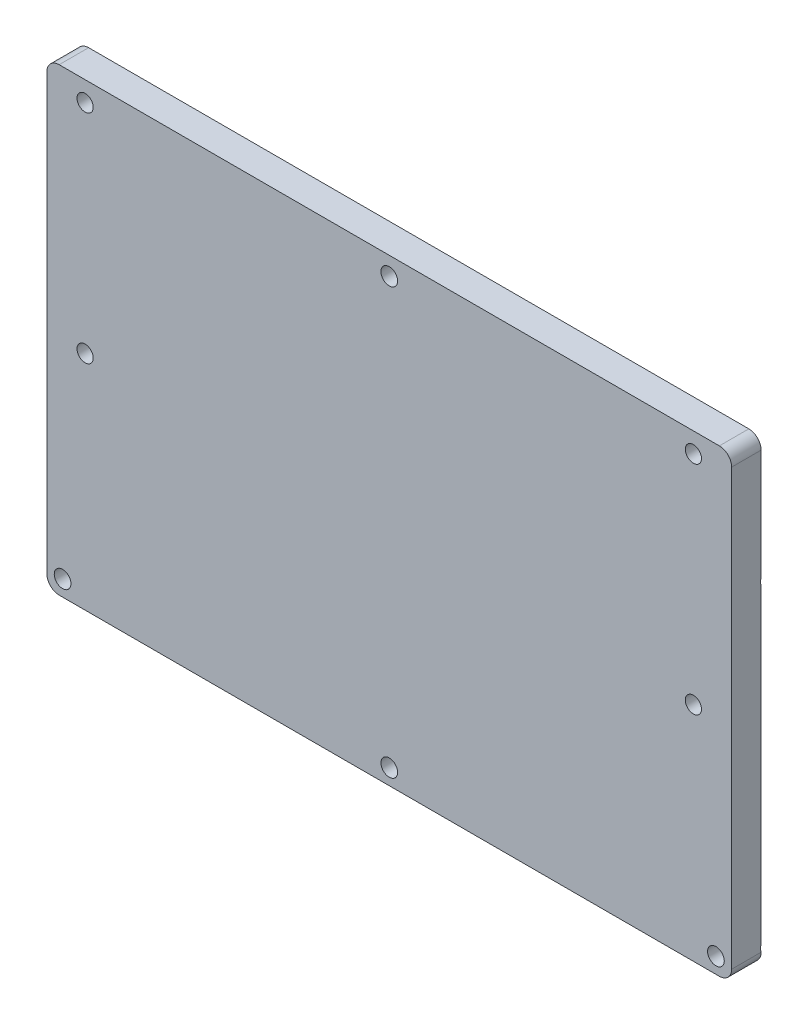
SolidWorks part; units mm, degrees
ref_plane "Front Plane" through (0, 0, 0) normal (0, 0, 1) x (1, 0, 0)
ref_plane "Top Plane" through (0, 0, 0) normal (0, 1, 0) x (1, 0, 0)
ref_plane "Right Plane" through (0, 0, 0) normal (1, 0, 0) x (0, 0, -1)
ref_plane "Plane1" through (0, 0, 0) normal (0, 0, -1) x (-1, 0, 0)
sketch "Sketch1" plane through (0, 0, 0) normal (0, 0, -1) x (-1, 0, 0)
  line L0 (-69.7, 93.82) -> (-69.7, 71.4262)
  line L1 (-69.7, 71.4262) -> (-69.7, 69.8138)
  line L2 (-69.7, 69.8138) -> (-69.7, 6.8062)
  line L3 (-69.7, 6.8062) -> (-69.7, 5.3)
  line L4 (-67.2, 2.8) -> (-65.6938, 2.8)
  line L5 (-65.6938, 2.8) -> (-0.8062, 2.8)
  line L6 (-0.8062, 2.8) -> (0.8062, 2.8)
  line L7 (0.8062, 2.8) -> (65.6938, 2.8)
  line L8 (65.6938, 2.8) -> (67.2, 2.8)
  line L9 (69.7, 5.3) -> (69.7, 6.8062)
  line L10 (69.7, 6.8062) -> (69.7, 69.8138)
  line L11 (69.7, 69.8138) -> (69.7, 71.4262)
  line L12 (69.7, 71.4262) -> (69.7, 93.82)
  line L13 (69.7, 93.82) -> (69.7, 96.32)
  line L14 (69.7, 96.32) -> (67.2, 96.32)
  line L15 (67.2, 96.32) -> (-67.2, 96.32)
  line L16 (-67.2, 96.32) -> (-69.7, 96.32)
  line L17 (-69.7, 96.32) -> (-69.7, 93.82)
  arc A0 (-69.7, 5.3) -> (-69.6973, 5.183) centre (-67.2, 5.3) ccw
  arc A1 (-67.317, 2.8027) -> (-69.6973, 5.183) centre (-67.2, 5.3) cw
  arc A2 (-67.317, 2.8027) -> (-67.2, 2.8) centre (-67.2, 5.3) ccw
  arc A3 (67.2, 2.8) -> (67.317, 2.8027) centre (67.2, 5.3) ccw
  arc A4 (69.6973, 5.183) -> (67.317, 2.8027) centre (67.2, 5.3) cw
  arc A5 (69.6973, 5.183) -> (69.7, 5.3) centre (67.2, 5.3) ccw
extrude "Boss-Extrude1" add sketch "Sketch1" against normal blind 6
ref_plane "Plane2" through (0, 70.62, 0) normal (0, 1, 0) x (1, 0, 0)
sketch "Sketch2" plane through (0, 70.62, 0) normal (0, 1, 0) x (1, 0, 0)
  line L0 (69.8002, 0.0002) -> (66.5, 0.0002)
  line L1 (66.5, 0.0002) -> (66.5, -3)
  line L2 (66.5, -3) -> (68.2, -3)
  line L3 (68.2, -3) -> (68.2, -1.6485)
  line L4 (68.2, -1.6485) -> (69.8002, 0.0002)
  line L5 (66.5, 0.0002) -> (66.5, -3) construction
revolve "Cut-Revolve1" cut sketch "Sketch2" angle 360 about L5
sketch "Sketch3" plane through (0, 70.62, 0) normal (0, 1, 0) x (1, 0, 0)
  line L0 (-63.1998, 0.0002) -> (-66.5, 0.0002)
  line L1 (-66.5, 0.0002) -> (-66.5, -3)
  line L2 (-66.5, -3) -> (-64.8, -3)
  line L3 (-64.8, -3) -> (-64.8, -1.6485)
  line L4 (-64.8, -1.6485) -> (-63.1998, 0.0002)
  line L5 (-66.5, 0.0002) -> (-66.5, -3) construction
revolve "Cut-Revolve2" cut sketch "Sketch3" angle 360 about L5
ref_plane "Plane3" through (0, 16, 0) normal (0, 1, 0) x (1, 0, 0)
sketch "Sketch4" plane through (0, 16, 0) normal (0, 1, 0) x (1, 0, 0)
  line L0 (-49, 4) -> (-56, 4)
  line L1 (-56, 4) -> (-56, 0)
  line L2 (-56, 0) -> (-49, 0)
  line L3 (-49, 0) -> (-49, 4)
  line L4 (-56, 4) -> (-56, -0.005) construction
revolve "Revolve1" [suppressed] add sketch "Sketch4" angle 360 about L4
sketch "Sketch5" plane through (0, 16, 0) normal (0, 1, 0) x (1, 0, 0)
  line L0 (63, 4) -> (56, 4)
  line L1 (56, 4) -> (56, 0)
  line L2 (56, 0) -> (63, 0)
  line L3 (63, 0) -> (63, 4)
  line L4 (56, 4) -> (56, -0.005) construction
revolve "Revolve2" [suppressed] add sketch "Sketch5" angle 360 about L4
ref_plane "Plane4" through (0, 82.62, 0) normal (0, 1, 0) x (1, 0, 0)
sketch "Sketch6" plane through (0, 82.62, 0) normal (0, 1, 0) x (1, 0, 0)
  line L0 (-49, 4) -> (-56, 4)
  line L1 (-56, 4) -> (-56, 0)
  line L2 (-56, 0) -> (-49, 0)
  line L3 (-49, 0) -> (-49, 4)
  line L4 (-56, 4) -> (-56, -0.005) construction
revolve "Revolve3" [suppressed] add sketch "Sketch6" angle 360 about L4
sketch "Sketch7" plane through (0, 82.62, 0) normal (0, 1, 0) x (1, 0, 0)
  line L0 (63, 4) -> (56, 4)
  line L1 (56, 4) -> (56, 0)
  line L2 (56, 0) -> (63, 0)
  line L3 (63, 0) -> (63, 4)
  line L4 (56, 4) -> (56, -0.005) construction
revolve "Revolve4" [suppressed] add sketch "Sketch7" angle 360 about L4
ref_plane "Plane5" through (0, 92.256, 0) normal (0, -1, 0) x (1, 0, 0)
sketch "Sketch8" plane through (0, 92.256, 0) normal (0, -1, 0) x (1, 0, 0)
  line L0 (65.91, 17) -> (61.91, 17)
  line L1 (61.91, 17) -> (61.91, 3)
  line L2 (61.91, 3) -> (65.91, 3)
  line L3 (65.91, 3) -> (65.91, 17)
  line L4 (61.91, 17.005) -> (61.91, 2.995) construction
revolve "Revolve5" add sketch "Sketch8" angle 360 about L4
sketch "Sketch9" plane through (0, 92.256, 0) normal (0, -1, 0) x (1, 0, 0)
  line L0 (-57.915, 17) -> (-61.915, 17)
  line L1 (-61.915, 17) -> (-61.915, 3)
  line L2 (-61.915, 3) -> (-57.915, 3)
  line L3 (-57.915, 3) -> (-57.915, 17)
  line L4 (-61.915, 17.005) -> (-61.915, 2.995) construction
revolve "Revolve6" add sketch "Sketch9" angle 360 about L4
ref_plane "Plane6" through (0, 48.06, 0) normal (0, -1, 0) x (1, 0, 0)
sketch "Sketch10" plane through (0, 48.06, 0) normal (0, -1, 0) x (1, 0, 0)
  line L0 (65.91, 17) -> (61.91, 17)
  line L1 (61.91, 17) -> (61.91, 3)
  line L2 (61.91, 3) -> (65.91, 3)
  line L3 (65.91, 3) -> (65.91, 17)
  line L4 (61.91, 17.005) -> (61.91, 2.995) construction
revolve "Revolve7" add sketch "Sketch10" angle 360 about L4
sketch "Sketch11" plane through (0, 48.06, 0) normal (0, -1, 0) x (1, 0, 0)
  line L0 (-57.915, 17) -> (-61.915, 17)
  line L1 (-61.915, 17) -> (-61.915, 3)
  line L2 (-61.915, 3) -> (-57.915, 3)
  line L3 (-57.915, 3) -> (-57.915, 17)
  line L4 (-61.915, 17.005) -> (-61.915, 2.995) construction
revolve "Revolve8" add sketch "Sketch11" angle 360 about L4
hole_wizard "CSK for #4 Flat Head Machine Screw (100)1" positions "Sketch13" profile "Sketch12" countersink size "#4" standard "ANSI Inch"
sketch "Sketch13" plane through (0, 0, 0) normal (0, 0, -1) x (-1, 0, 0)
  point P0 (66.5, 6)
  point P1 (0, 6)
  point P2 (-66.5, 6)
  point P3 (0, 92.62)
sketch "Sketch12" plane through (-66.5, 6, 0) normal (1, 0, 0) x (0, 1, 0)
  line L0 (0, 0) -> (0, 17)
  line L1 (0, 17) -> (1.7, 17)
  line L2 (1.7, 17) -> (1.7, 1.6485)
  line L3 (1.7, 1.6485) -> (3.3, 0)
  line L5 (3.3, 0) -> (0, 0)
  line L6 (-1.7, 1.6485) -> (-3.3, 0) construction
  line L11 (0, -6.35) -> (0, 107.95) construction
  dimension "Thru Hole Dia." = 3.4
  dimension "Thru Hole Depth" = 17
  dimension "Near C'Sink Dia." = 6.6
  dimension "Near C'Sink Angle" = 88.29
hole_wizard "#6 Clearance Hole1" positions "Sketch15" profile "Sketch14" hole size "#6" standard "ANSI Inch"
sketch "Sketch15" plane through (0, 0, 17) normal (0, 0, 1) x (1, 0, 0)
  point P0 (-61.915, 48.06)
  point P1 (61.91, 48.06)
  point P2 (-61.915, 92.256)
  point P3 (61.91, 92.256)
sketch "Sketch14" plane through (-61.915, 48.06, 17) normal (1, 0, 0) x (0, -1, 0)
  line L0 (0, 0) -> (0, 6)
  line L1 (0, 6) -> (2.1, 6)
  line L2 (2.1, 6) -> (2.1, 0)
  line L5 (2.1, 0) -> (0, 0)
  line L10 (0, 6) -> (-2.1, 6) construction
  line L11 (0, -6.35) -> (0, 107.95) construction
  dimension "Hole Dia." = 4.2
  dimension "Hole Depth" = 6
  dimension "Drill Angle" = 180
hole_wizard "3/8 Clearance Hole1" [suppressed] positions "Sketch17" profile "Sketch16" hole size "3/8" standard "ANSI Inch"
sketch "Sketch17" [suppressed] plane through (0, 0, -4) normal (0, 0, -1) x (-1, 0, 0)
  point P0 (-56, 82.62)
  point P1 (56, 82.62)
  point P2 (-56, 16)
  point P3 (56, 16)
sketch "Sketch16" plane through (56, 82.62, -4) normal (1, 0, 0) x (0, 1, 0)
  line L0 (0, 0) -> (0, 0.79)
  line L1 (0, 0.79) -> (5.1, 0.79)
  line L2 (5.1, 0.79) -> (5.1, 0)
  line L5 (5.1, 0) -> (0, 0)
  line L10 (0, 0.79) -> (-5.1, 0.79) construction
  line L11 (0, -6.35) -> (0, 107.95) construction
  dimension "Hole Dia." = 10.2
  dimension "Hole Depth" = 0.79
  dimension "Drill Angle" = 180
fillet "Fillet1" [suppressed] radius 1.5
fillet "Fillet2" radius 2.5 2 edges at (69.7, 96.32, 3) (-69.7, 96.32, 3)
hole_wizard "M4x0.7 Tapped Hole1" positions "Sketch18" profile "Sketch19" tap size "M4x0.7" standard "ANSI Metric"
sketch "Sketch18" plane through (0, 0, 6) normal (0, 0, 1) x (1, 0, 0)
  point P0 (-61.915, 48.06)
  point P3 (-61.915, 92.256)
  point P6 (61.91, 92.256)
  point P9 (61.91, 48.06)
sketch "Sketch19" plane through (-61.915, 48.06, 6) normal (1, 0, 0) x (0, -1, 0)
  line L0 (0, 0) -> (0, 6.0002)
  line L1 (0, 6.0002) -> (1.65, 6.0002)
  line L2 (1.65, 6.0002) -> (1.65, 0)
  line L5 (1.65, 0) -> (0, 0)
  line L11 (0, -6.35) -> (0, 107.95) construction
  dimension "Thru Tap Drill Dia." = 3.3
  dimension "Thru Tap Drill Depth" = 6.0002
cosmetic thread "Hole Thread1" parameters "D2"=4
cosmetic thread "Hole Thread2" parameters "D2"=4
cosmetic thread "Hole Thread3" parameters "D2"=4
cosmetic thread "Hole Thread4" parameters "D2"=4
sketch "Sketch20" plane through (0, 0, 6) normal (0, 0, 1) x (1, 0, 0)
  line L1 (79.7995, 101.8661) -> (-81.7945, 101.8661)
  line L2 (79.7995, 101.8661) -> (79.7995, 33.7871)
  line L3 (79.7995, 33.7871) -> (-81.7945, 33.7871)
  line L4 (-81.7945, 101.8661) -> (-81.7945, 33.7871)
  line L5 (79.7995, 101.8661) -> (-81.7945, 33.7871) construction
  line L6 (79.7995, 33.7871) -> (-81.7945, 101.8661) construction
  point P0 (-0.9975, 67.8266)
extrude "Cut-Extrude1" cut sketch "Sketch20" along normal through all
